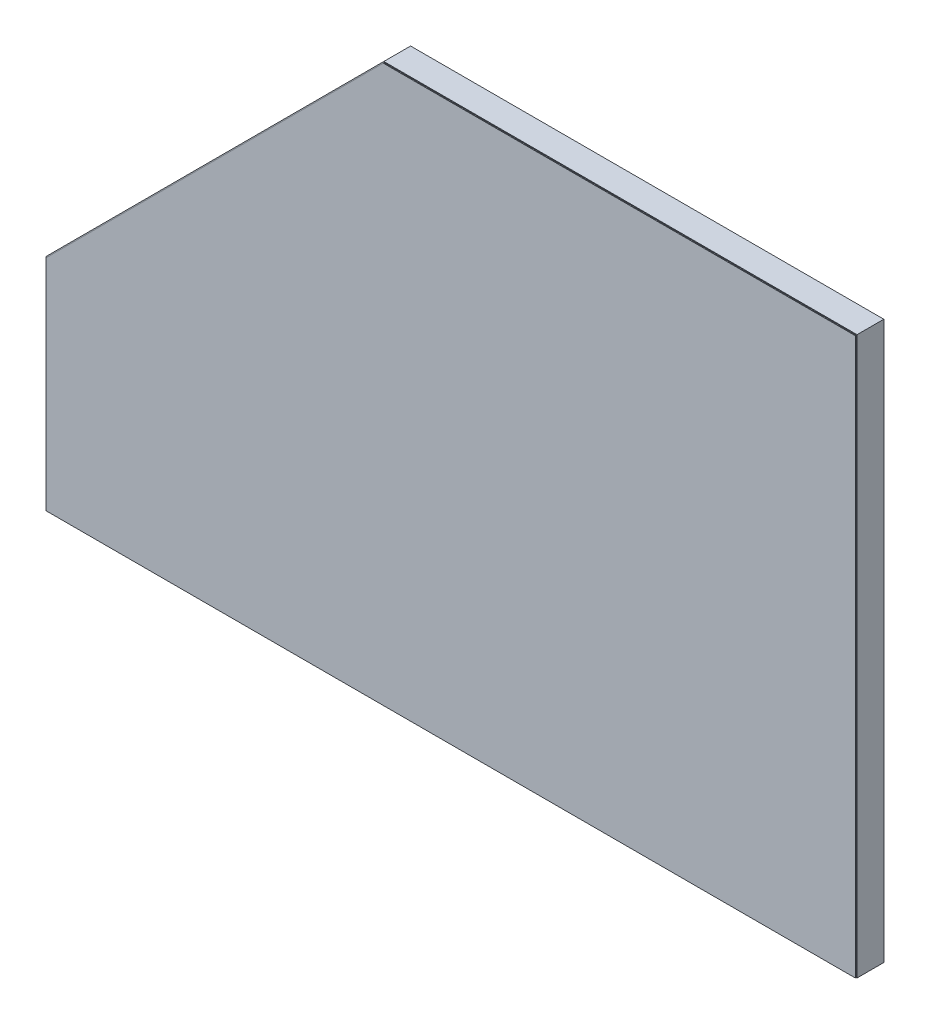
SolidWorks part; units mm, degrees
other "Elemento de detalle1"
other "Elemento de detalle2"
other "Carpeta de soldadura"
other "Cordón de soldadura1"
other "Cordón de soldadura2"
ref_plane "Alzado" through (0, 0, 0) normal (0, 0, 1) x (1, 0, 0)
ref_plane "Planta" through (0, 0, 0) normal (0, 1, 0) x (1, 0, 0)
ref_plane "Vista lateral" through (0, 0, 0) normal (1, 0, 0) x (0, 0, -1)
sketch "Croquis1" plane through (0, 0, 0) normal (0, 0, 1) x (1, 0, 0)
  line L0 (0, 0) -> (768, 0)
  line L1 (768, 0) -> (768, 528)
  line L2 (768, 528) -> (320, 528)
  line L3 (320, 528) -> (0, 208)
  line L4 (0, 208) -> (0, 0)
  dimension "D1" = 768
  dimension "D2" = 528
  dimension "D3" = 448
  dimension "D4" = 208
extrude "Saliente-Extruir1" add sketch "Croquis1" along normal blind 0.8357
sketch "Croquis3" plane through (0, 0, 0) normal (0, 0, -1) x (-1, 0, 0)
  line L0 (0.8357, 0) -> (0.8357, 208.3461)
  line L1 (0.8357, 208.3461) -> (-319.6539, 528.8357)
  line L2 (-319.6539, 528.8357) -> (-768.8357, 528.8357)
  line L3 (-768.8357, 528.8357) -> (-768.8357, 0)
  line L4 (0.8357, 0) -> (0, 0)
  line L5 (0, 0) -> (0, 208)
  line L6 (0, 208) -> (-320, 528)
  line L7 (-320, 528) -> (-768, 528)
  line L8 (-768, 528) -> (-768, 0)
  line L9 (-768, 0) -> (0, 0)
  line L10 (0, 0) -> (0, 208)
  line L11 (0, 208) -> (-320, 528)
  line L12 (-320, 528) -> (-768, 528)
  line L13 (-768, 528) -> (-768, 0)
  line L15 (-768.8357, 0) -> (-768, 0)
  dimension "D1" = 0
  dimension "D2" = 0.8357
extrude "Saliente-Extruir2" add sketch "Croquis3" along normal blind 25.4 separate body
